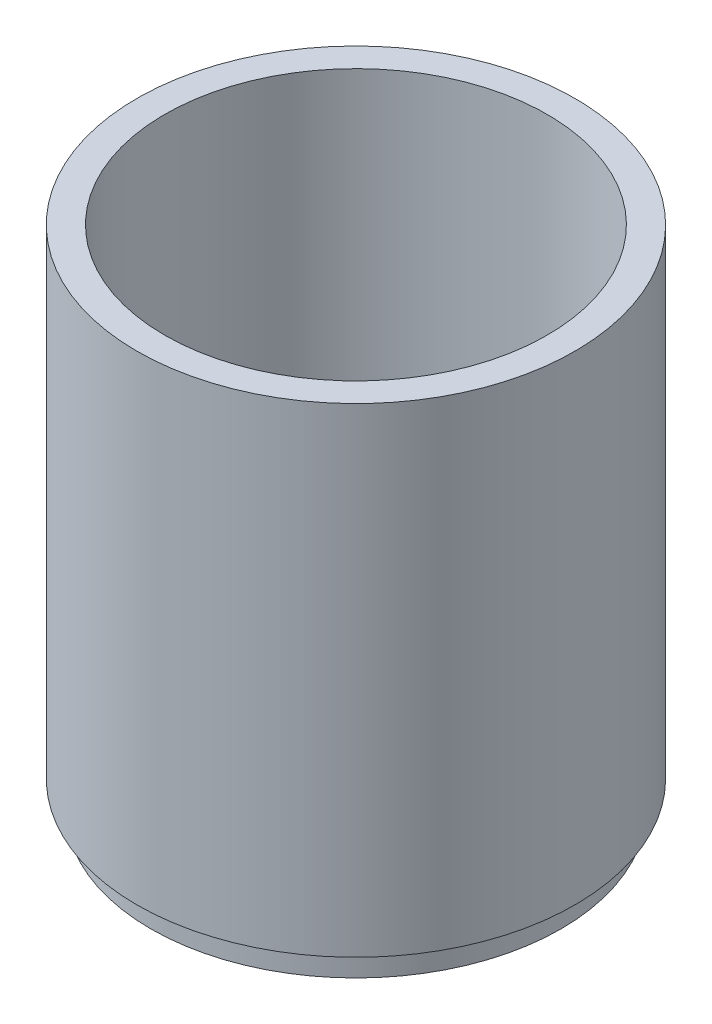
SolidWorks part; units mm, degrees
ref_plane "Front Plane" through (0, 0, 0) normal (0, 0, 1) x (1, 0, 0)
ref_plane "Top Plane" through (0, 0, 0) normal (0, 1, 0) x (1, 0, 0)
ref_plane "Right Plane" through (0, 0, 0) normal (1, 0, 0) x (0, 0, -1)
sketch "Sketch1" plane through (0, 0, 0) normal (0, 1, 0) x (1, 0, 0)
  circle A0 centre (0, 0) radius 7.4
  circle A1 centre (0, 0) radius 6.4
  dimension "D1" = 14.8
  dimension "D2" = 12.8
extrude "Boss-Extrude1" add sketch "Sketch1" along normal blind 1
sketch "Sketch2" plane through (0, 1, 0) normal (0, 1, 0) x (1, 0, 0)
  circle A0 centre (0, 0) radius 7.9
  circle A1 centre (0, 0) radius 6.9
  dimension "D1" = 15.8
  dimension "D2" = 13.8
extrude "Boss-Extrude2" add sketch "Sketch2" along normal blind 17.3
